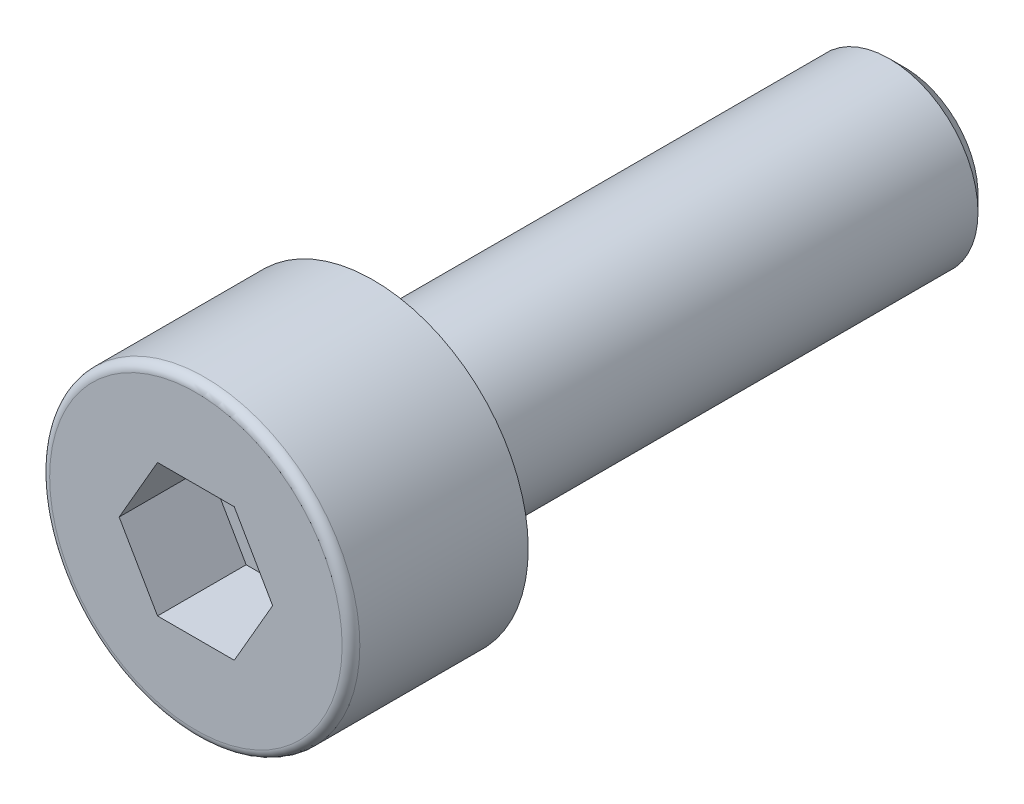
SolidWorks part; units mm, degrees
material "STAINLESS STEEL, 316S16"
ref_plane "Front Plane" through (0, 0, 0) normal (0, 0, 1) x (1, 0, 0)
ref_plane "Top Plane" through (0, 0, 0) normal (0, 1, 0) x (1, 0, 0)
ref_plane "Right Plane" through (0, 0, 0) normal (1, 0, 0) x (0, 0, -1)
sketch "Sketch1" plane through (0, 0, 0) normal (0, -1, 0) x (1, 0, 0)
  line L0 (0, 4) -> (0, -12) construction
  line L1 (0, -12) -> (-2, -12)
  line L2 (-2, -12) -> (-2, 0)
  line L3 (-2, 0) -> (-3.5, 0)
  line L4 (-3.5, 0) -> (-3.5, 3.8)
  line L5 (-3.3, 4) -> (0, 4)
  line L6 (0, 4) -> (0, -12)
  arc A0 (-3.5, 3.8) -> (-3.3, 4) centre (-3.3, 3.8) cw
  dimension "D4" = 0.2
  dimension "D1" = 4
  dimension "D2" = 7
  dimension "D3" = 4
  dimension "L" = 12
revolve "Revolve1" add sketch "Sketch1" angle 360 mid plane about L0
cosmetic thread "Thread" parameters "D1"=12, "D2"=3.22
sketch "Sketch2" plane through (0, 0, 4) normal (0, 0, 1) x (1, 0, 0)
  line L1 (1.7321, 0) -> (0.866, 1.5)
  line L2 (0.866, 1.5) -> (-0.866, 1.5)
  line L3 (-0.866, 1.5) -> (-1.7321, 0)
  line L4 (-1.7321, 0) -> (-0.866, -1.5)
  line L5 (-0.866, -1.5) -> (0.866, -1.5)
  line L6 (0.866, -1.5) -> (1.7321, 0)
  circle A0 centre (0, 0) radius 1.5 construction
  dimension "D1" = 3
extrude "Cut-Extrude1" cut sketch "Sketch2" against normal blind 2
chamfer "Chamfer1" distance 0.35 angle 45 1 edges at (2, 0, -12)
equation "\"D4@Sketch1\" = (\"D1@Sketch1\"/2)/10"
